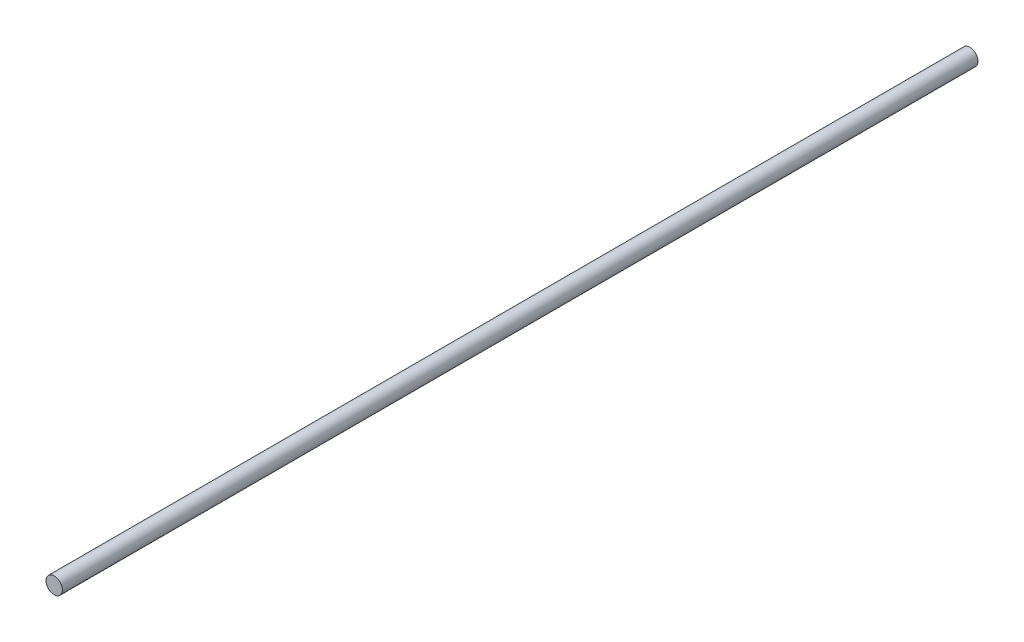
SolidWorks part; units mm, degrees
ref_plane "Front" through (0, 0, 0) normal (0, 0, 1) x (1, 0, 0)
ref_plane "Top" through (0, 0, 0) normal (0, 1, 0) x (1, 0, 0)
ref_plane "Right" through (0, 0, 0) normal (1, 0, 0) x (0, 0, -1)
sketch "Sketch1" plane through (0, 0, 0) normal (0, 0, 1) x (1, 0, 0)
  circle A0 centre (0, 0) radius 3.175
extrude "Boss-Extrude1" add sketch "Sketch1" along normal blind 355.6
